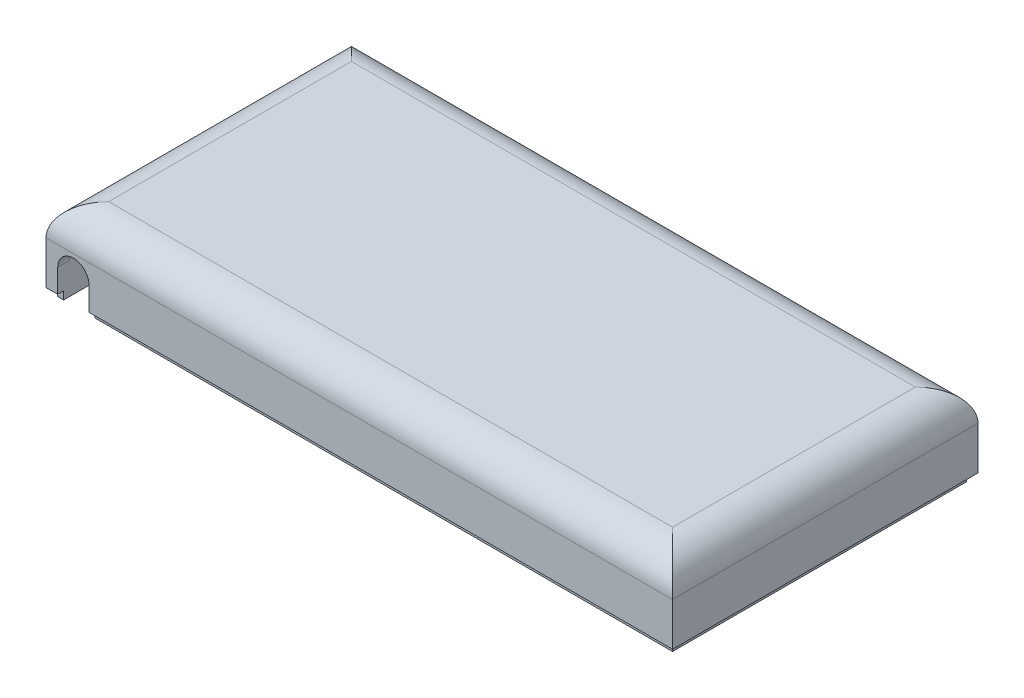
SolidWorks part; units mm, degrees
material "ABS"
ref_plane "Front Plane" through (0, 0, 0) normal (0, 0, 1) x (1, 0, 0)
ref_plane "Top Plane" through (0, 0, 0) normal (0, 1, 0) x (1, 0, 0)
ref_plane "Right Plane" through (0, 0, 0) normal (1, 0, 0) x (0, 0, -1)
sketch "Sketch1" plane through (0, 0, 0) normal (0, 1, 0) x (1, 0, 0)
  line L1 (-38.5, -18) -> (38.5, -18)
  line L2 (-38.5, -18) -> (-38.5, 18)
  line L3 (-38.5, 18) -> (38.5, 18)
  line L4 (38.5, -18) -> (38.5, 18)
  line L5 (-38.5, -18) -> (38.5, 18) construction
  line L6 (-38.5, 18) -> (38.5, -18) construction
  line L7 (40, -19.5) -> (-40, -19.5)
  line L8 (40, -19.5) -> (40, 19.5)
  line L9 (40, 19.5) -> (-40, 19.5)
  line L10 (-40, -19.5) -> (-40, 19.5)
  line L11 (40, -19.5) -> (-40, 19.5) construction
  line L12 (40, 19.5) -> (-40, -19.5) construction
  point P0 (0, 0)
  point P5 (0, 0)
  dimension "D1" = 36
  dimension "D2" = 77
  dimension "D3" = 1.5
  dimension "D4" = 1.5
extrude "Boss-Extrude1" add sketch "Sketch1" along normal blind 9
sketch "Sketch2" plane through (0, 9, 0) normal (0, 1, 0) x (1, 0, 0)
  line L1 (40, 19.5) -> (-40, 19.5)
  line L2 (40, 19.5) -> (40, -19.5)
  line L3 (40, -19.5) -> (-40, -19.5)
  line L4 (-40, 19.5) -> (-40, -19.5)
  line L5 (40, 19.5) -> (-40, -19.5) construction
  line L6 (40, -19.5) -> (-40, 19.5) construction
  point P0 (0, 0)
extrude "Boss-Extrude2" add sketch "Sketch2" along normal blind 1.5
sketch "Sketch4" plane through (0, 0, 0) normal (0, -1, 0) x (1, 0, 0)
  line L1 (-38.5, 18) -> (38.5, 18) construction
  line L2 (40, -19.5) -> (-40, -19.5)
  line L3 (40, -19.5) -> (40, 19.5)
  line L4 (40, 19.5) -> (-40, 19.5)
  line L5 (-40, -19.5) -> (-40, 19.5)
  line L6 (40, -19.5) -> (-40, 19.5) construction
  line L8 (40, 19.5) -> (-40, -19.5) construction
  line L9 (39.25, -18.75) -> (-39.25, -18.75)
  line L10 (39.25, -18.75) -> (39.25, 18.75)
  line L11 (39.25, 18.75) -> (-39.25, 18.75)
  line L12 (-39.25, -18.75) -> (-39.25, 18.75)
  line L13 (39.25, -18.75) -> (-39.25, 18.75) construction
  line L14 (39.25, 18.75) -> (-39.25, -18.75) construction
  line L15 (-38.5, -18) -> (-38.5, 18) construction
  point P0 (0, 0)
  point P5 (0, 0)
  dimension "D1" = 0.75
  dimension "D2" = 0.75
extrude "Cut-Extrude1" cut sketch "Sketch4" against normal blind 1
fillet "Fillet1" radius 4 4 edges at (0, 10.5, -19.5) (40, 10.5, 0) (0, 10.5, 19.5) (-40, 10.5, 0)
sketch "Sketch5" plane through (0, 0, 19.5) normal (0, 0, 1) x (1, 0, 0)
  line L0 (-36.5, -2) -> (-36.5, 4) construction
  line L1 (39.25, 1) -> (-39.25, 1) construction
  line L2 (-38.5, -2) -> (-38.5, 4)
  line L3 (-34.5, -2) -> (-34.5, 4)
  line L4 (40, 1) -> (-40, 1) construction
  line L5 (-40, 6.5) -> (-40, 1) construction
  arc A0 (-38.5, -2) -> (-34.5, -2) centre (-36.5, -2) ccw
  arc A1 (-34.5, 4) -> (-38.5, 4) centre (-36.5, 4) ccw
  point P4 (-36.5, 1)
  point P13 (-36.5, 6)
  dimension "D1" = 4
  dimension "D2" = 1.5
  dimension "D3" = 5
extrude "Cut-Extrude2" cut sketch "Sketch5" against normal up to next
